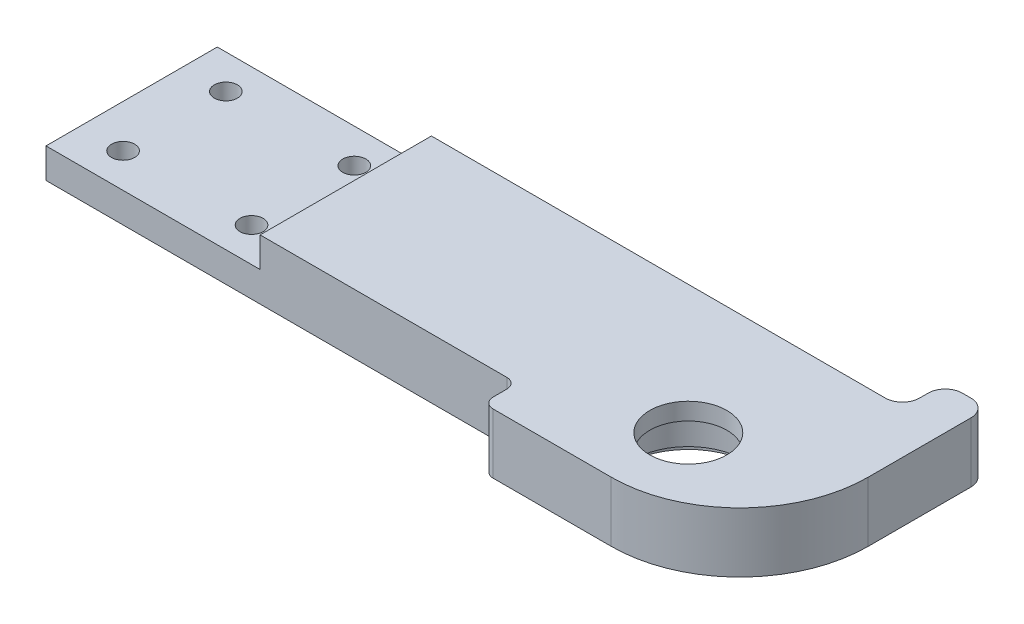
SolidWorks part; units mm, degrees
ref_plane "Front Plane" through (0, 0, 0) normal (0, 0, 1) x (1, 0, 0)
ref_plane "Top Plane" through (0, 0, 0) normal (0, 1, 0) x (1, 0, 0)
ref_plane "Right Plane" through (0, 0, 0) normal (1, 0, 0) x (0, 0, -1)
sketch "Sketch1" plane through (0, 0, 0) normal (0, 1, 0) x (1, 0, 0)
  line L0 (85, 0) -> (85, 5) construction
  line L1 (0, 0) -> (55, 0)
  line L2 (0, 0) -> (0, 20)
  line L3 (0, 20) -> (85, 20)
  line L4 (85, 0) -> (85, 20)
  line L5 (85, 5) -> (70, 5) construction
  line L8 (85, 0) -> (85, -4)
  line L9 (85, -4) -> (55, -4)
  line L10 (55, 0) -> (55, -4)
  circle A0 centre (70, 5) radius 4.5
  dimension "D4" = 9
  dimension "D1" = 20
  dimension "D2" = 85
  dimension "D3" = 5
  dimension "D5" = 15
  dimension "D6" = 30
  dimension "D7" = 4
extrude "Boss-Extrude1" add sketch "Sketch1" along normal blind 7
sketch "Sketch2" plane through (0, 0, 0) normal (0, -1, 0) x (1, 0, 0)
  line L0 (85, -20) -> (0, -20) construction
  line L1 (0, 0) -> (25, 0)
  line L2 (0, 0) -> (0, -20)
  line L3 (0, -20) -> (25, -20)
  line L4 (25, 0) -> (25, -20)
  dimension "D1" = 25
extrude "Cut-Extrude1" cut sketch "Sketch2" against normal blind 3.5
sketch "Sketch3" plane through (0, 3.5, 0) normal (0, -1, 0) x (1, 0, 0)
  line L0 (0, -10) -> (25, -10) construction
  line L1 (0, 0) -> (0, -20) construction
  line L2 (25, -20) -> (25, 0) construction
  line L4 (5, -16) -> (20, -16) construction
  line L5 (5, -16) -> (5, -4) construction
  line L6 (5, -4) -> (20, -4) construction
  line L7 (20, -16) -> (20, -4) construction
  line L8 (5, -16) -> (20, -4) construction
  line L9 (5, -4) -> (20, -16) construction
  circle A0 centre (5, -4) radius 1.35
  circle A1 centre (20, -4) radius 1.35
  circle A2 centre (20, -16) radius 1.35
  circle A3 centre (5, -16) radius 1.35
  point P6 (12.5, -10)
  dimension "D1" = 15
  dimension "D2" = 12
extrude "Cut-Extrude2" cut sketch "Sketch3" against normal blind 14
fillet "Fillet2" radius 1.2 2 edges at (55, 3.5, 4) (55, 3.5, 0)
sketch "Sketch4" plane through (0, 7, 0) normal (0, 1, 0) x (1, 0, 0)
  circle A0 centre (70, 5) radius 7.5
  dimension "D1" = 15
extrude "Cut-Extrude3" cut sketch "Sketch4" against normal blind 1
sketch "Sketch5" plane through (0, 6, 0) normal (0, 1, 0) x (1, 0, 0)
  circle A0 centre (70, 5) radius 6.5
  dimension "D1" = 13
extrude "Cut-Extrude4" cut sketch "Sketch5" against normal blind 4
fillet "Fillet3" radius 15 1 edges at (85, 3.5, 4)
sketch "Sketch6" plane through (0, 7, 0) normal (0, 1, 0) x (1, 0, 0)
  line L1 (85, 20) -> (80, 20)
  line L2 (85, 20) -> (85, 25)
  line L3 (85, 25) -> (80, 25)
  line L4 (80, 20) -> (80, 25)
  dimension "D1" = 5
  dimension "D2" = 5
extrude "Boss-Extrude2" add sketch "Sketch6" against normal up to surface (7 mm away) up to face at (57.0118, 0, -3.9882)
fillet "Fillet4" radius 2 3 edges at (85, 3.5, -25) (80, 3.5, -25) (80, 3.5, -20)
mirror "Mirror1" about plane through (0, 0, 0) normal (0, -1, 0) of bodies 106
sketch "Sketch7" plane through (0, 7, 0) normal (0, 1, 0) x (1, 0, 0)
  line L1 (-17.46, 38.5679) -> (93.2286, 38.5679)
  line L2 (-17.46, 38.5679) -> (-17.46, -16.7324)
  line L3 (-17.46, -16.7324) -> (93.2286, -16.7324)
  line L4 (93.2286, 38.5679) -> (93.2286, -16.7324)
extrude "Cut-Extrude5" cut sketch "Sketch7" against normal blind 7
